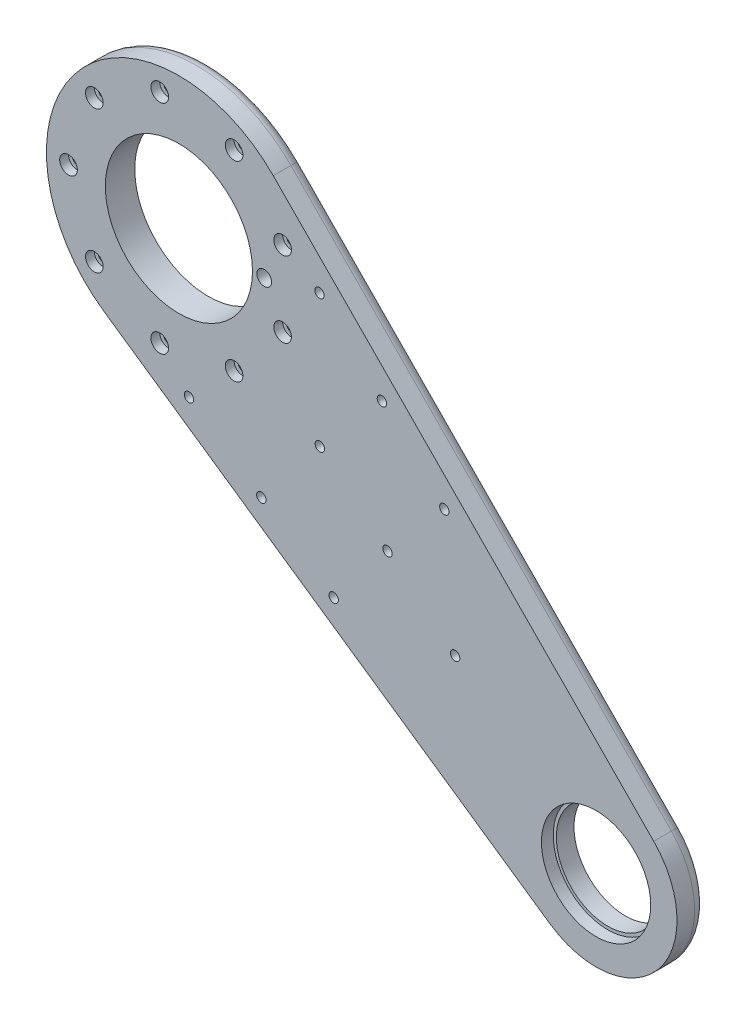
SolidWorks part; units mm, degrees
material "ABS"
ref_plane "Front Plane" through (0, 0, 0) normal (0, 0, 1) x (1, 0, 0)
ref_plane "Top Plane" through (0, 0, 0) normal (0, 1, 0) x (1, 0, 0)
ref_plane "Right Plane" through (0, 0, 0) normal (1, 0, 0) x (0, 0, -1)
sketch "Sketch1" plane through (0, 0, 0) normal (0, 0, 1) x (1, 0, 0)
  line L0 (141.7182, -118.9157) -> (13.1607, -272.1246) construction
  line L1 (26.7138, 26.3177) -> (155.9656, -104.8796) construction
  line L2 (-25.5349, -37.0536) -> (126.1136, -141.5596)
  line L3 (32.0566, 31.5812) -> (161.3084, -99.6161)
  line L4 (-21.2791, -30.878) -> (130.3694, -135.384) construction
  arc A0 (32.0566, 31.5812) -> (-25.5349, -37.0536) centre (0, 0) ccw
  arc A1 (126.1136, -141.5596) -> (161.3084, -99.6161) centre (141.7182, -118.9157) ccw
  circle A5 centre (0, 0) radius 25 construction
  circle A6 centre (0, 0) radius 37.5 construction
  circle A7 centre (141.7182, -118.9157) radius 17.5
  circle A8 centre (70.8591, -59.4579) radius 1.6
  circle A9 centre (93.8404, -78.7415) radius 1.6
  circle A10 centre (47.8778, -40.1742) radius 1.6
  circle A11 centre (141.7182, -118.9157) radius 20 construction
  circle A12 centre (47.768, 4.9466) radius 1.6
  circle A14 centre (3.4233, -47.9013) radius 1.6
  circle A16 centre (68.9739, -16.2739) radius 1.6
  circle A17 centre (90.1797, -37.4944) radius 1.6
  circle A18 centre (28.0039, -65.1001) radius 1.6
  circle A19 centre (52.5844, -82.2989) radius 1.6
  circle A20 centre (116.8218, -98.0251) radius 1.6 construction
  point P16 (141.7182, -118.9157)
extrude "Boss-Extrude1" add sketch "Sketch1" along normal blind 10
sketch "Sketch2" plane through (0, 0, 10) normal (0, 0, 1) x (1, 0, 0)
  line L0 (0, 0) -> (141.7182, 0) construction
  circle A0 centre (0, 0) radius 25
  circle A2 centre (29, 0) radius 2.5
  circle A3 centre (-37.5, 0) radius 1.6
  circle A4 centre (0, 0) radius 37.5 construction
  circle A5 centre (-28.7267, 24.1045) radius 1.6
  circle A6 centre (-6.5118, 36.9303) radius 1.6
  circle A7 centre (18.75, 32.476) radius 1.6
  circle A8 centre (35.2385, 12.8258) radius 1.6
  circle A9 centre (35.2385, -12.8258) radius 1.6
  circle A10 centre (18.75, -32.476) radius 1.6
  circle A11 centre (-6.5118, -36.9303) radius 1.6
  circle A12 centre (-28.7267, -24.1045) radius 1.6
  point P30 (0, 0)
  dimension "D1" = 50
  dimension "D2" = 5
  dimension "D3" = 3.2
  dimension "D4" = 29
  dimension "D5" = 9
extrude "Cut-Extrude1" cut sketch "Sketch2" against normal through all
sketch "Sketch3" plane through (0, 0, 10) normal (0, 0, 1) x (1, 0, 0)
  circle A0 centre (141.7182, -118.9157) radius 18.5625
  dimension "D1" = 37.125
extrude "Cut-Extrude2" cut sketch "Sketch3" against normal blind 4
sketch "Sketch4" plane through (0, 0, 10) normal (0, 0, 1) x (1, 0, 0)
  circle A0 centre (-28.7267, 24.1045) radius 3
  circle A1 centre (-6.5118, 36.9303) radius 3
  circle A2 centre (18.75, 32.476) radius 3
  circle A3 centre (35.2385, 12.8258) radius 3
  circle A4 centre (35.2385, -12.8258) radius 3
  circle A5 centre (18.75, -32.476) radius 3
  circle A6 centre (-6.5118, -36.9303) radius 3
  circle A7 centre (-28.7267, -24.1045) radius 3
  circle A8 centre (-37.5, 0) radius 3
  dimension "D1" = 6
  dimension "D2" = 6
  dimension "D3" = 6
  dimension "D4" = 6
  dimension "D5" = 6
  dimension "D6" = 6
  dimension "D7" = 6
  dimension "D8" = 6
  dimension "D9" = 6
extrude "Cut-Extrude3" cut sketch "Sketch4" against normal blind 3
fillet "Fillet1" radius 4 4 edges at (162.7844, -136.5924, 0) (50.2894, -89.3066, 0) (-34.472, 28.9254, 0) (96.6825, -34.0174, 0)
equation "\"thighLength\"=185"
equation "\"legLength\"=200"
equation "\"m3Thru\"=3.2"
equation "\"m4Thru\"=4.3"
equation "\"D3@Sketch2\"=\"m3Thru\""
equation "\"shoulder5mm\"=5.1"
equation "\"6706out\"=37.125"
equation "\"D1@Sketch3\"=\"6706out\""
equation "\"6706in\"=30"
equation "\"6904out\"=30.125"
equation "\"6904in\"=17"
